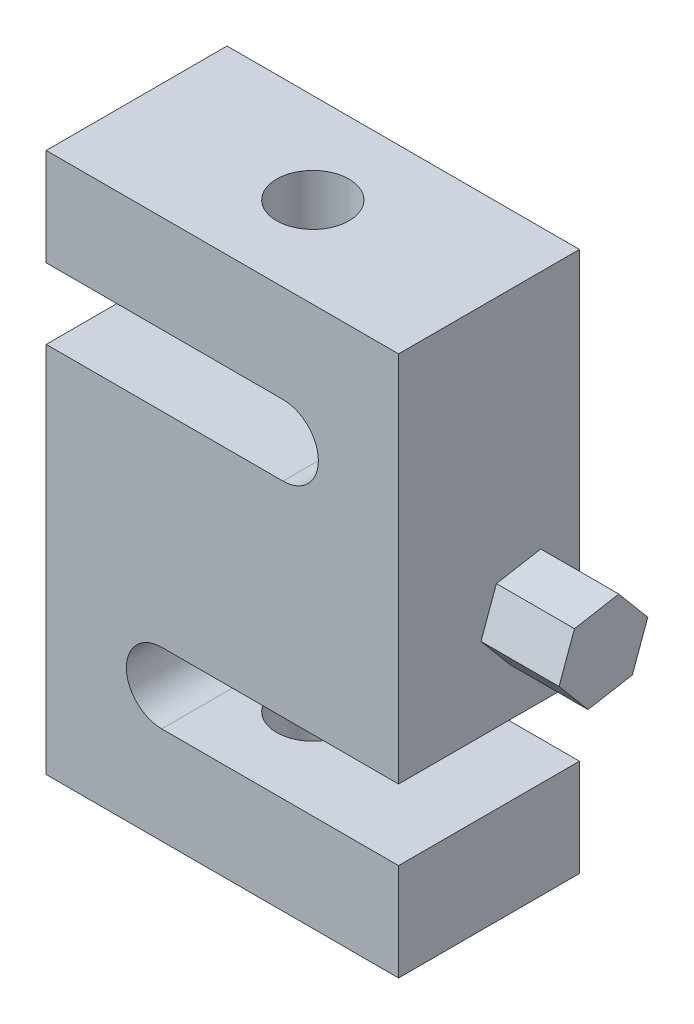
SolidWorks part; units mm, degrees
ref_plane "Front Plane" through (0, 0, 0) normal (0, 0, 1) x (1, 0, 0)
ref_plane "Top Plane" through (0, 0, 0) normal (0, 1, 0) x (1, 0, 0)
ref_plane "Right Plane" through (0, 0, 0) normal (1, 0, 0) x (0, 0, -1)
sketch "Sketch1" plane through (0, 0, 0) normal (0, 0, 1) x (1, 0, 0)
  line L1 (24.8285, -38.0873) -> (-24.8285, -38.0873)
  line L2 (24.8285, -38.0873) -> (24.8285, 38.0873)
  line L3 (24.8285, 38.0873) -> (-24.8285, 38.0873)
  line L4 (-24.8285, -38.0873) -> (-24.8285, 38.0873)
  line L5 (24.8285, -38.0873) -> (-24.8285, 38.0873) construction
  line L6 (24.8285, 38.0873) -> (-24.8285, -38.0873) construction
  line L7 (-24.8285, 24.3713) -> (8.5471, 24.3713)
  line L8 (-24.8285, 24.3713) -> (-24.8285, 14.4145)
  line L9 (-24.8285, 14.4145) -> (8.5471, 14.4145)
  line L11 (24.8285, -24.3713) -> (-8.5471, -24.3713)
  line L12 (24.8285, -24.3713) -> (24.8285, -14.4145)
  line L13 (24.8285, -14.4145) -> (-8.5471, -14.4145)
  arc A0 (-8.5471, -14.4145) -> (-8.5471, -24.3713) centre (-8.5471, -19.3929) ccw
  arc A1 (8.5471, 24.3713) -> (8.5471, 14.4145) centre (8.5471, 19.3929) cw
  point P0 (0, 0)
  dimension "D7" = 33.3756
  dimension "D1" = 76.1746
  dimension "D2" = 49.657
  dimension "D3" = 9.9568
  dimension "D4" = 9.9568
  dimension "D5" = 13.716
  dimension "D6" = 13.716
  dimension "D8" = 33.3756
extrude "Boss-Extrude1" add sketch "Sketch1" along normal blind 25.4889 contours L7 A1 L9 L4 L1 L2 L11 A0 L13 L3
sketch "Sketch2" plane through (24.8285, 0, 0) normal (1, 0, 0) x (0, 0, -1)
  line L0 (-25.4889, -14.4145) -> (0, -14.4145) construction
  line L1 (-11.7006, 3.1508) -> (-13.8738, -2.8157)
  line L2 (-13.8738, -2.8157) -> (-9.7932, -7.6811)
  line L3 (-9.7932, -7.6811) -> (-3.5394, -6.5798)
  line L4 (-3.5394, -6.5798) -> (-1.3662, -0.6133)
  line L5 (-1.3662, -0.6133) -> (-5.4468, 4.2521)
  line L6 (-5.4468, 4.2521) -> (-11.7006, 3.1508)
  line L7 (0, -14.4145) -> (0, 38.0873) construction
  circle A0 centre (-7.62, -1.7145) radius 5.4993 construction
  dimension "D1" = 12.7
  dimension "D2" = 6.35
  dimension "D3" = 7.62
extrude "Boss-Extrude2" add sketch "Sketch2" along normal blind 10.9982
sketch "Sketch3" plane through (0, 38.0873, 0) normal (0, 1, 0) x (1, 0, 0)
  line L0 (-24.8285, -12.7445) -> (24.8285, -12.7445) construction
  line L1 (0, 0) -> (0, -25.4889) construction
  line L4 (24.8285, 0) -> (-24.8285, 0)
  line L5 (-24.8285, 0) -> (-24.8285, -25.4889)
  line L6 (-24.8285, -25.4889) -> (24.8285, -25.4889)
  line L7 (24.8285, -25.4889) -> (24.8285, 0)
  line L8 (24.8285, 0) -> (-24.8285, 0)
  line L9 (-24.8285, 0) -> (-24.8285, -25.4889)
  line L10 (-24.8285, -25.4889) -> (24.8285, -25.4889)
  line L11 (24.8285, -25.4889) -> (24.8285, 0)
  circle A0 centre (0, -12.7445) radius 3.175
  point P9 (0, -12.7445)
  dimension "D2" = 6.35
  dimension "D1" = 0
hole_wizard "Tap Drill for M12x1.75 Tap1" positions "Sketch3" profile "Sketch4" hole size "M12x1.75" standard "ANSI Metric"
sketch "Sketch4" plane through (0, 38.0873, 12.7445) normal (1, 0, 0) x (0, 0, 1)
  line L0 (0, 0) -> (0, 22.1144)
  line L1 (0, 22.1144) -> (5.1, 19.05)
  line L2 (5.1, 19.05) -> (5.1, 0)
  line L5 (5.1, 0) -> (0, 0)
  line L10 (0, 22.1144) -> (-5.1, 19.05) construction
  line L11 (0, -6.35) -> (0, 107.95) construction
  dimension "Hole Dia." = 10.2
  dimension "Hole Depth" = 19.05
  dimension "Drill Angle" = 118
hole_wizard "Tap Drill for M12x1.75 Tap2" positions "Sketch5" profile "Sketch6" hole size "M12x1.75" standard "ANSI Metric"
sketch "Sketch5" plane through (0, -38.0873, 0) normal (0, -1, 0) x (-1, 0, 0)
  line L0 (-24.8285, -12.7445) -> (24.8285, -12.7445) construction
  line L1 (0, 0) -> (0, -25.4889) construction
  line L12 (-24.8285, -25.4889) -> (24.8285, -25.4889) construction
  line L13 (24.8285, -25.4889) -> (24.8285, 0) construction
  line L14 (-24.8285, -25.4889) -> (-24.8285, 0) construction
  circle A0 centre (0, -12.7445) radius 3.175
  point P9 (0, -12.7445)
  dimension "D2" = 6.35
sketch "Sketch6" plane through (0, -38.0873, 12.7445) normal (1, 0, 0) x (0, 0, -1)
  line L0 (0, 0) -> (0, 22.1144)
  line L1 (0, 22.1144) -> (5.1, 19.05)
  line L2 (5.1, 19.05) -> (5.1, 0)
  line L5 (5.1, 0) -> (0, 0)
  line L10 (0, 22.1144) -> (-5.1, 19.05) construction
  line L11 (0, -6.35) -> (0, 107.95) construction
  dimension "Hole Dia." = 10.2
  dimension "Hole Depth" = 19.05
  dimension "Drill Angle" = 118
